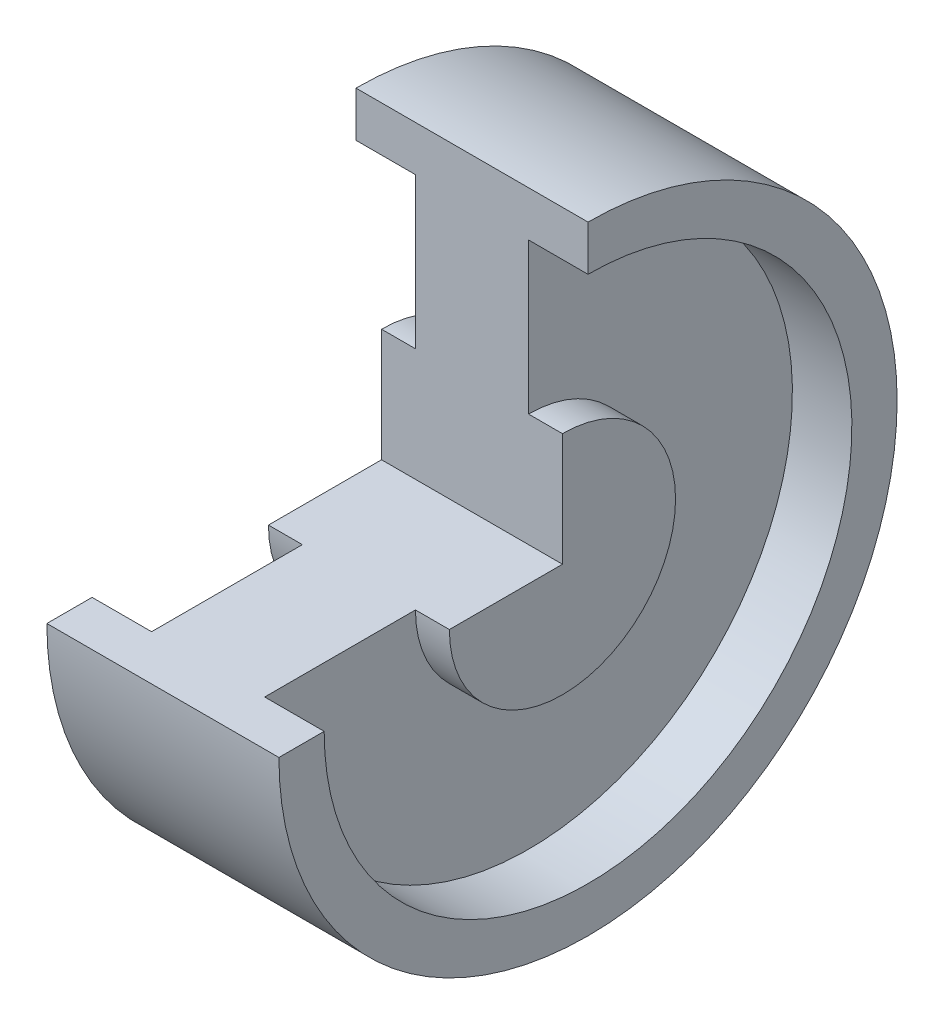
SolidWorks part; units mm, degrees
ref_plane "Front Plane" through (0, 0, 0) normal (0, 0, 1) x (1, 0, 0)
ref_plane "Top Plane" through (0, 0, 0) normal (0, 1, 0) x (1, 0, 0)
ref_plane "Right Plane" through (0, 0, 0) normal (1, 0, 0) x (0, 0, -1)
sketch "Sketch1" plane through (0, 0, 0) normal (0, 0, 1) x (1, 0, 0)
  line L0 (-29.6882, 67.9677) -> (31.8728, 67.9677)
  line L1 (31.8728, 67.9677) -> (31.8728, 55.9677)
  line L2 (31.8728, 55.9677) -> (16.0923, 55.9677)
  line L3 (16.0923, 55.9677) -> (16.0923, 15.9677)
  line L4 (16.0923, 15.9677) -> (25.0923, 15.9677)
  line L5 (25.0923, 15.9677) -> (25.0923, -14.0323)
  line L6 (25.0923, -14.0323) -> (-22.9077, -14.0323)
  line L7 (1.0923, 67.9677) -> (1.0923, -19.1039) construction
  line L8 (-29.6882, 67.9677) -> (-29.6882, 55.9677)
  line L9 (-29.6882, 55.9677) -> (-13.9077, 55.9677)
  line L10 (-13.9077, 55.9677) -> (-13.9077, 15.9677)
  line L11 (-13.9077, 15.9677) -> (-22.9077, 15.9677)
  line L12 (-22.9077, 15.9677) -> (-22.9077, -14.0323)
  point P15 (1.0923, -14.0323)
  dimension "D1" = 40
  dimension "D2" = 48
  dimension "D3" = 30
  dimension "D4" = 12
  dimension "D5" = 15
revolve "Revolve3" add sketch "Sketch1" angle 270 about L6
